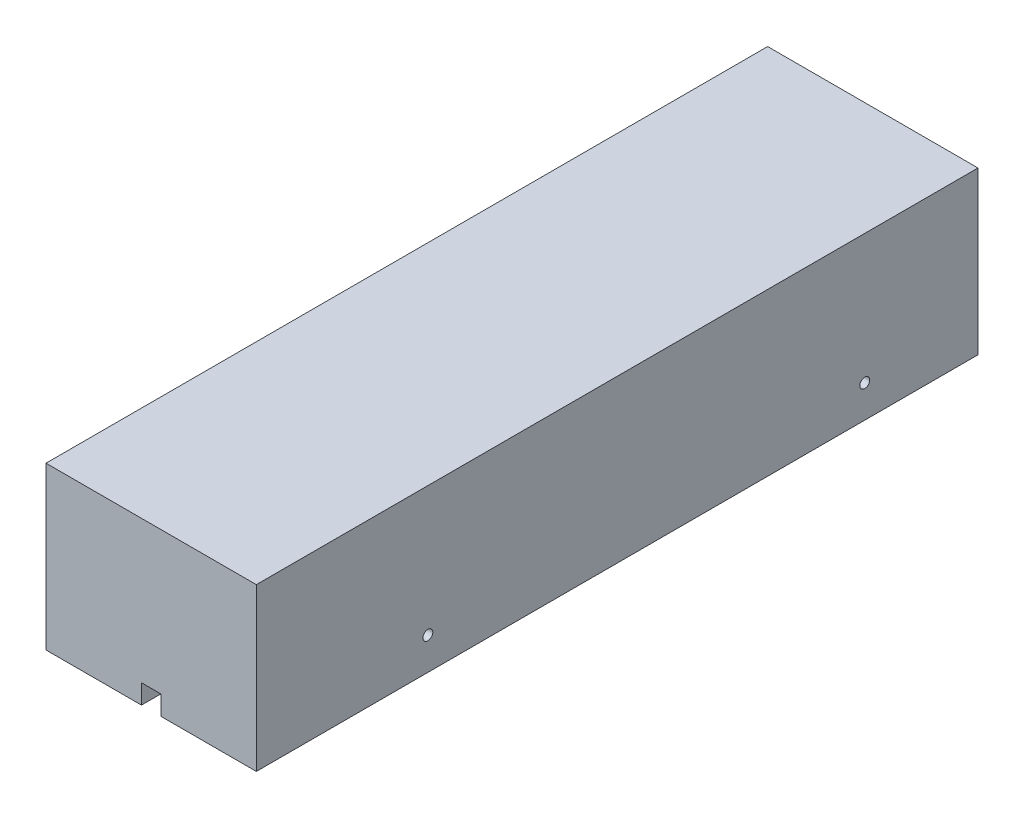
SolidWorks part; units mm, degrees
material "Balsa"
ref_plane "Front Plane" through (0, 0, 0) normal (0, 0, 1) x (1, 0, 0)
ref_plane "Top Plane" through (0, 0, 0) normal (0, 1, 0) x (1, 0, 0)
ref_plane "Right Plane" through (0, 0, 0) normal (1, 0, 0) x (0, 0, -1)
sketch "Sketch1" plane through (0, 0, 0) normal (0, 0, 1) x (1, 0, 0)
  line L1 (-32.5, 0) -> (32.5, 0)
  line L2 (-32.5, 0) -> (-32.5, 50)
  line L3 (-32.5, 50) -> (32.5, 50)
  line L4 (32.5, 0) -> (32.5, 50)
  dimension "D1" = 65
  dimension "D2" = 50
extrude "Balsa Block" add sketch "Sketch1" along normal blind 223
sketch "Sketch2" plane through (0, 0, 223) normal (0, 0, 1) x (1, 0, 0)
  line L0 (-32.5, 0) -> (32.5, 0) construction
  line L1 (-3, 0) -> (3, 0)
  line L2 (-3, 0) -> (-3, 6)
  line L3 (-3, 6) -> (3, 6)
  line L4 (3, 0) -> (3, 6)
  dimension "D1" = 6
  dimension "D2" = 6
extrude "Screw Eye Slot" cut sketch "Sketch2" against normal through all
sketch "Sketch3" plane through (0, 0, 0) normal (0, 0, -1) x (-1, 0, 0)
  line L0 (32.5, 0) -> (3, 0) construction
  circle A0 centre (0, 29) radius 9.55
  dimension "D1" = 19.1
  dimension "D2" = 29
extrude "CO2 Cartridge Hole" cut sketch "Sketch3" against normal blind 52
sketch "Sketch4" plane through (32.5, 0, 0) normal (1, 0, 0) x (0, 0, -1)
  line L0 (-223, 0) -> (0, 0) construction
  line L1 (0, 0) -> (0, 50) construction
  circle A0 centre (-170, 10) radius 1.525
  circle A1 centre (-35, 10) radius 1.525
  dimension "D4" = 3.05
  dimension "D1" = 10
  dimension "D2" = 135
  dimension "D3" = 35
extrude "Axle Hole Cut Out" cut sketch "Sketch4" against normal through all
sketch "Sketch5" plane through (0, 50, 0) normal (0, 1, 0) x (1, 0, 0)
  line L0 (32.5, 0) -> (-32.5, 0) construction
  line L1 (0, 0) -> (0, -229.7898) construction
  line L2 (-14.55, 0) -> (-14.55, -51.1732)
  line L3 (-17.1047, -57.8491) -> (-25.4453, -67.1509)
  line L4 (-28, -73.8268) -> (-28, -120)
  line L5 (-14.4879, 48.8908) -> (-14.4879, 49.7327) construction
  line L6 (28, -73.8268) -> (28, -120)
  line L7 (17.1047, -57.8491) -> (25.4453, -67.1509)
  line L8 (14.55, 0) -> (14.55, -51.1732)
  line L9 (-14.7766, 49.831) -> (-14.7766, 50.2789) construction
  line L10 (-9.55, 0) -> (-9.55, -52) construction
  line L11 (9.55, -52) -> (9.55, 0) construction
  arc A0 (-25.4453, -67.1509) -> (-28, -73.8268) centre (-18, -73.8268) ccw
  arc A1 (-14.55, -51.1732) -> (-17.1047, -57.8491) centre (-24.55, -51.1732) cw
  arc A2 (14.55, -51.1732) -> (17.1047, -57.8491) centre (24.55, -51.1732) ccw
  arc A3 (25.4453, -67.1509) -> (28, -73.8268) centre (18, -73.8268) cw
  spline S0 degree 3 poles (-28, -120) (-27.6859, -126.0056) (-27.1636, -135.9946) (-19.7034, -144.9636) (-13.3488, -154.8578) (-14.7766, -154.2092) (-14.7766, -173.3072) (-14.4879, -181.2754) (-14.4879, -195.7718) (-8.4397, -210.8954) (-2.3915, -226.019) knots 0 0 0 0 0.179945 0.299298 0.299298 0.625194 0.625194 0.690626 0.690626 1 1 1 1
  spline S1 degree 3 poles (28, -120) (27.6859, -126.0056) (27.1636, -135.9946) (19.7034, -144.9636) (13.3488, -154.8578) (14.7766, -154.2092) (14.7766, -173.3072) (14.4879, -181.2754) (14.4879, -195.7718) (8.4397, -210.8954) (2.3915, -226.019) knots 0 0 0 0 0.179945 0.299298 0.299298 0.625194 0.625194 0.690626 0.690626 1 1 1 1
  spline S2 degree 3 poles (-14.55, 0) (-14.55, -18.3333) (-14.55, -36.6667) (-14.55, -55) knots 0 0 0 0 1 1 1 1
  spline S3 degree 3 poles (14.55, 0) (14.55, -18.3333) (14.55, -36.6667) (14.55, -55) knots 0 0 0 0 1 1 1 1
  dimension "D2" = 5
  dimension "D1" = 5
sketch "Sketch6" plane through (0, 0, 0) normal (1, 0, 0) x (0, 0, -1)
  line L1 (-52, 19.45) -> (0, 19.45) construction
  line L3 (0, 35.543) -> (0, -35.543) construction
  line L10 (-210, 10.9116) -> (-210, 0)
  line L13 (-210, 0) -> (-22.7709, 0)
  spline S0 degree 3 poles (-210, 10.9116) (-202.7227, 13.8598) (-188.783, 19.5071) (-143.7313, 22.444) (-85.5632, 16.1988) (-63.4626, 33.1745) (-61.6089, 55.2214) (-24.8176, 48.2515) (0, 43.55) knots 0 0 0 0 0.060945 0.11674 0.333018 0.333018 0.550088 1 1 1 1
  spline S1 degree 3 poles (-22.7709, 0) (-21.942, 3.2613) (-20.3664, 9.4604) (-11.2641, 16.1435) (-4.1106, 15.068) (0, 14.45) knots 0 0 0 0 0.32075 0.609686 1 1 1 1
  dimension "D3" = 5
  dimension "D1" = 210
  dimension "D2" = 5
sketch "Sketch7" plane through (0, 0, 0) normal (0, 0, -1) x (-1, 0, 0)
  line L0 (18.8348, 21.5) -> (32.5, 21.5)
  line L2 (-18.8348, 21.5) -> (-32.5, 21.5)
  line L5 (0, 0) -> (0, 64.6236) construction
  arc A0 (13.8783, 27.1579) -> (-13.8783, 27.1579) centre (0, 29) ccw
  arc A1 (-13.8783, 27.1579) -> (-18.8348, 21.5) centre (-18.8348, 26.5) cw
  arc A2 (13.8783, 27.1579) -> (18.8348, 21.5) centre (18.8348, 26.5) ccw
  dimension "D1" = 14
  dimension "D3" = 5
  dimension "D2" = 21.5
  dimension "D4" = 65
sketch "Sketch8" plane through (0, 0, 0) normal (1, 0, 0) x (0, 0, -1)
  line L0 (-202.5076, 10) -> (-187, 14)
  line L1 (-187, 14) -> (-187, 6)
  line L2 (-187, 6) -> (-202, 6)
  line L3 (-210, 0) -> (-22.7709, 0) construction
  line L6 (-210, 10.9116) -> (-210, 0) construction
  arc A0 (-202.5076, 10) -> (-202, 6) centre (-202, 8.0322) ccw
  dimension "D1" = 15
  dimension "D2" = 6
  dimension "D3" = 8
  dimension "D4" = 10
  dimension "D5" = 8
